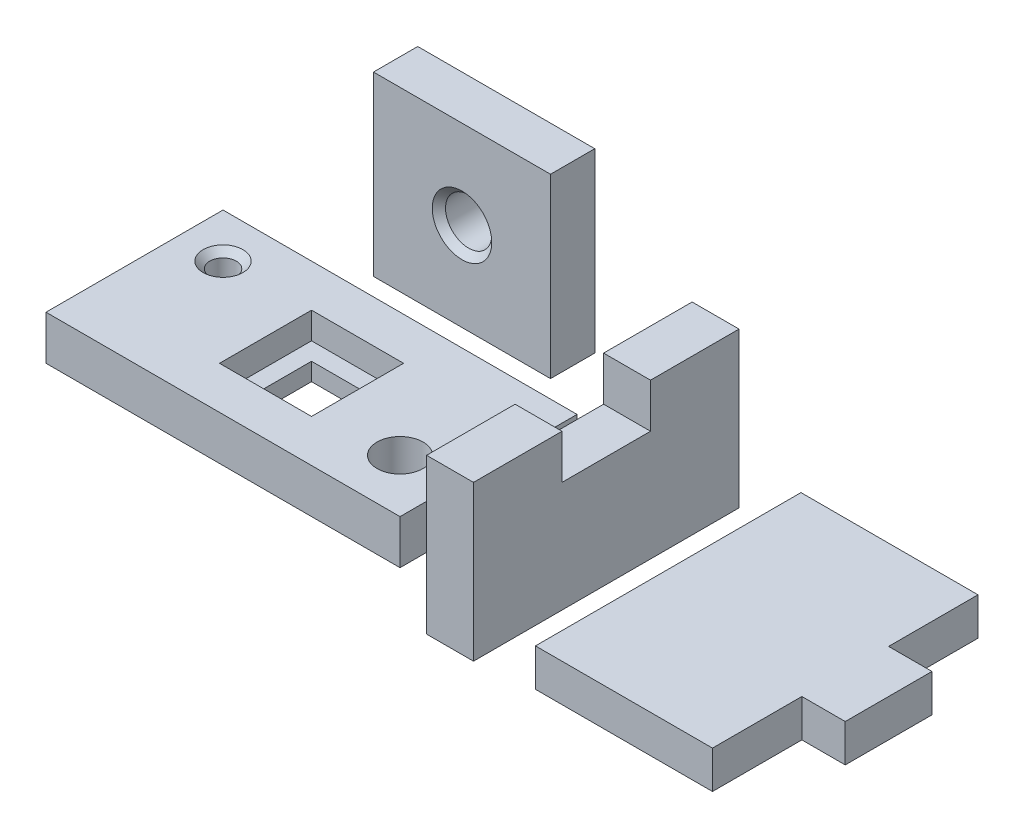
SolidWorks part; units mm, degrees
ref_plane "Front Plane" through (0, 0, 0) normal (0, 0, 1) x (1, 0, 0)
ref_plane "Top Plane" through (0, 0, 0) normal (0, 1, 0) x (1, 0, 0)
ref_plane "Right Plane" through (0, 0, 0) normal (1, 0, 0) x (0, 0, -1)
sketch "Sketch1" plane through (0, 0, 0) normal (0, 1, 0) x (1, 0, 0)
  line L1 (-20, 10) -> (20, 10)
  line L2 (-20, 10) -> (-20, -10)
  line L3 (-20, -10) -> (20, -10)
  line L4 (20, 10) -> (20, -10)
  line L5 (-20, 10) -> (20, -10) construction
  line L6 (-20, -10) -> (20, 10) construction
  point P0 (0, 0)
  dimension "D1" = 40
  dimension "D2" = 20
extrude "Boss-Extrude1" add sketch "Sketch1" along normal blind 5
sketch "Sketch2" plane through (0, 5, 0) normal (0, 1, 0) x (1, 0, 0)
  line L0 (-20, 10) -> (-20, -10) construction
  line L1 (20, 10) -> (-20, 10) construction
  line L2 (20, -10) -> (20, 10) construction
  line L3 (-20, -10) -> (20, -10) construction
  circle A0 centre (-15, 5) radius 1.5
  circle A1 centre (14, -4) radius 2.6
  dimension "D1" = 3
  dimension "D2" = 5.2
  dimension "D3" = 5
  dimension "D4" = 5
  dimension "D5" = 6
  dimension "D6" = 6
extrude "Cut-Extrude1" cut sketch "Sketch2" against normal blind 5
chamfer "Chamfer1" distance 0.75 angle 45 2 edges at (-15, 5, -3.5) (-15, 0, -3.5)
chamfer "Chamfer2" distance 1 angle 45 1 edges at (14, 0, 6.6)
sketch "Sketch3" plane through (0, 5, 0) normal (0, 1, 0) x (1, 0, 0)
  line L1 (-3.2, 3.2) -> (3.2, 3.2)
  line L2 (-3.2, 3.2) -> (-3.2, -3.2)
  line L3 (-3.2, -3.2) -> (3.2, -3.2)
  line L4 (3.2, 3.2) -> (3.2, -3.2)
  line L5 (-3.2, 3.2) -> (3.2, -3.2) construction
  line L6 (-3.2, -3.2) -> (3.2, 3.2) construction
  point P0 (0, 0)
  dimension "D1" = 6.4
  dimension "D2" = 6.4
extrude "Cut-Extrude2" cut sketch "Sketch3" against normal blind 5
sketch "Sketch4" plane through (0, 0, 0) normal (0, 1, 0) x (1, 0, 0)
  line L0 (20, -10) -> (20, 10) construction
  line L1 (28, 15) -> (33.299, 15)
  line L2 (28, 15) -> (28, -15)
  line L3 (28, -15) -> (33.299, -15)
  line L4 (33.299, 15) -> (33.299, -15)
  line L5 (28, 15) -> (33.299, -15) construction
  line L6 (28, -15) -> (33.299, 15) construction
  point P0 (30.6495, 0)
  dimension "D1" = 5.299
  dimension "D2" = 30
  dimension "D3" = 8
extrude "Boss-Extrude2" add sketch "Sketch4" along normal blind 17.5 separate body
sketch "Sketch5" plane through (33.299, 0, 0) normal (1, 0, 0) x (0, 0, -1)
  line L0 (-15, 17.5) -> (15, 17.5) construction
  line L1 (-5, 22.5) -> (5, 22.5)
  line L2 (-5, 22.5) -> (-5, 12.5)
  line L3 (-5, 12.5) -> (5, 12.5)
  line L4 (5, 22.5) -> (5, 12.5)
  line L5 (-5, 22.5) -> (5, 12.5) construction
  line L6 (-5, 12.5) -> (5, 22.5) construction
  point P0 (0, 17.5)
  dimension "D1" = 10
  dimension "D2" = 10
extrude "Cut-Extrude3" cut sketch "Sketch5" against normal blind 17.5
sketch "Sketch6" plane through (0, 0, 0) normal (0, 1, 0) x (1, 0, 0)
  line L1 (40.299, 15) -> (60.299, 15)
  line L2 (40.299, 15) -> (40.299, -15)
  line L3 (40.299, -15) -> (60.299, -15)
  line L4 (60.299, 15) -> (60.299, -15)
  line L5 (33.299, -15) -> (33.299, -5) construction
  point P4 (40.299, 0)
  dimension "D1" = 20
  dimension "D2" = 30
  dimension "D3" = 7
extrude "Boss-Extrude3" add sketch "Sketch6" along normal blind 5 separate body
sketch "Sketch7" plane through (0, 5, 0) normal (0, 1, 0) x (1, 0, 0)
  line L0 (60.299, -15) -> (60.299, 15) construction
  line L1 (60.299, 4.9) -> (65.199, 4.9)
  line L2 (60.299, 4.9) -> (60.299, -4.9)
  line L3 (60.299, -4.9) -> (65.199, -4.9)
  line L4 (65.199, 4.9) -> (65.199, -4.9)
  point P6 (60.299, 0)
  dimension "D1" = 4.9
  dimension "D2" = 9.8
extrude "Boss-Extrude4" add sketch "Sketch7" against normal blind 5
sketch "Sketch8" plane through (0, 0, 0) normal (0, 1, 0) x (1, 0, 0)
  line L0 (20, 10) -> (-20, 10) construction
  line L1 (-10, 17) -> (10, 17)
  line L2 (-10, 17) -> (-10, 22)
  line L3 (-10, 22) -> (10, 22)
  line L4 (10, 17) -> (10, 22)
  point P4 (0, 17)
  dimension "D1" = 20
  dimension "D2" = 5
  dimension "D3" = 7
extrude "Boss-Extrude5" add sketch "Sketch8" along normal blind 20 separate body
sketch "Sketch9" plane through (0, 0, -22) normal (0, 0, -1) x (-1, 0, 0)
  line L0 (0, 20) -> (0, 0) construction
  line L1 (-10, 20) -> (10, 20) construction
  circle A0 centre (0, 10) radius 2.61
  dimension "D1" = 5.22
extrude "Cut-Extrude4" cut sketch "Sketch9" against normal blind 20
chamfer "Chamfer4" distance 0.75 angle 45 8 edges at (50.299, 0, 15) (60.299, 0, 9.95) (62.749, 0, 4.9) (65.199, 0, 0) (62.749, 0, -4.9) (60.299, 0, -9.95) (50.299, 0, -15) (40.299, 0, 0)
chamfer "Chamfer5" distance 0.75 angle 45 1 edges at (-2.61, 10, -17)
sketch "Sketch11" plane through (0, 5, 0) normal (0, 1, 0) x (1, 0, 0)
  line L0 (-3.2, 3.2) -> (-3.2, -3.2) construction
  line L1 (-5.2, 5.2) -> (5.2, 5.2)
  line L2 (-5.2, 5.2) -> (-5.2, -5.2)
  line L3 (-5.2, -5.2) -> (5.2, -5.2)
  line L4 (5.2, 5.2) -> (5.2, -5.2)
  line L5 (-5.2, 5.2) -> (5.2, -5.2) construction
  line L6 (-5.2, -5.2) -> (5.2, 5.2) construction
  line L7 (3.2, 3.2) -> (-3.2, 3.2) construction
  point P0 (0, 0)
  dimension "D1" = 2
  dimension "D2" = 2
extrude "Cut-Extrude5" cut sketch "Sketch11" against normal offset from surface (3 mm away) 2 up to face at (0, 0, 0)
equation "\"D2@Sketch3\"=\"D1@Sketch3\""
equation "\"D2@Sketch11\"=\"D1@Sketch11\""
